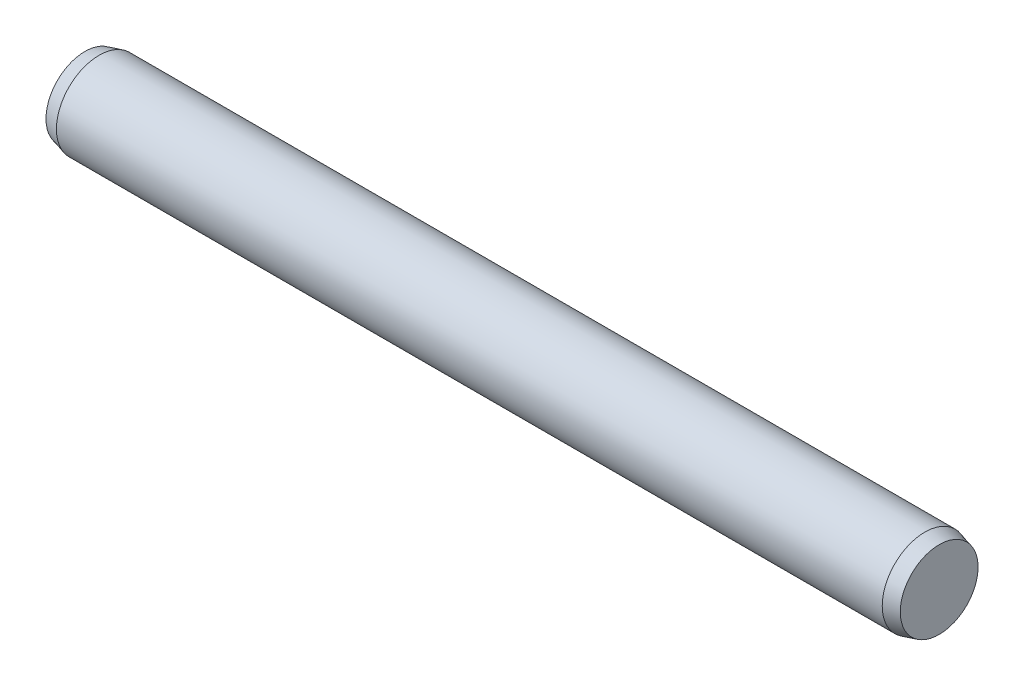
SolidWorks part; units mm, degrees
material "Alloy Steel"
ref_plane "Plane1" through (0, 0, 0) normal (0, 0, 1) x (1, 0, 0)
ref_plane "Plane2" through (0, 0, 0) normal (0, 1, 0) x (1, 0, 0)
ref_plane "Plane3" through (0, 0, 0) normal (1, 0, 0) x (0, 0, -1)
other "Configuration Table"
sketch "Sketch1" plane through (0, 0, 0) normal (0, 0, 1) x (1, 0, 0)
  line L1 (-6.35, 0) -> (107.95, 0) construction
  line L2 (0, 0) -> (30, 0)
  line L3 (30, 0) -> (30, 1.366)
  line L4 (30, 1.366) -> (29.5, 1.5)
  line L5 (29.5, 1.5) -> (0.5, 1.5)
  line L6 (0, 1.366) -> (0, 0)
  line L7 (0, 1.366) -> (0.5, 1.5)
  dimension "Chamfer_len" = 0.5
  dimension "D3" = 15
  dimension "Diameter" = 3
  dimension "D1" = 0.5
  dimension "D2" = 15
  dimension "Length" = 30
revolve "Base-Revolve" add sketch "Sketch1" angle 360 about L1
equation "\"D3@Sketch1\" = 15.0"
equation "\"D1@Sketch1\" = \"Chamfer_len@Sketch1\""
equation "\"D2@Sketch1\" = \"D3@Sketch1\""
